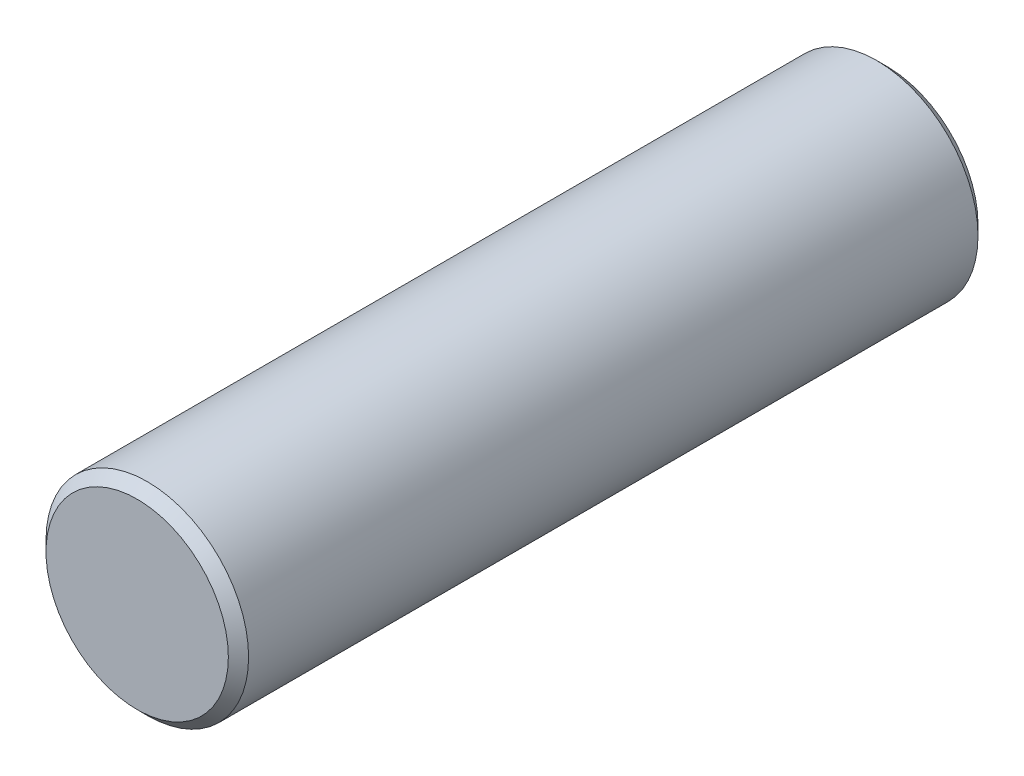
SolidWorks part; units mm, degrees
ref_plane "Front Plane" through (0, 0, 0) normal (0, 0, 1) x (1, 0, 0)
ref_plane "Top Plane" through (0, 0, 0) normal (0, 1, 0) x (1, 0, 0)
ref_plane "Right Plane" through (0, 0, 0) normal (1, 0, 0) x (0, 0, -1)
sketch "Sketch1" plane through (0, 0, 0) normal (0, 0, 1) x (1, 0, 0)
  circle A0 centre (0, 0) radius 254
  dimension "D1" = 508
extrude "Boss-Extrude1" add sketch "Sketch1" along normal blind 1879.6
chamfer "Chamfer1" distance 25.4 angle 45 2 edges at (254, 0, 0) (254, 0, 1879.6)
